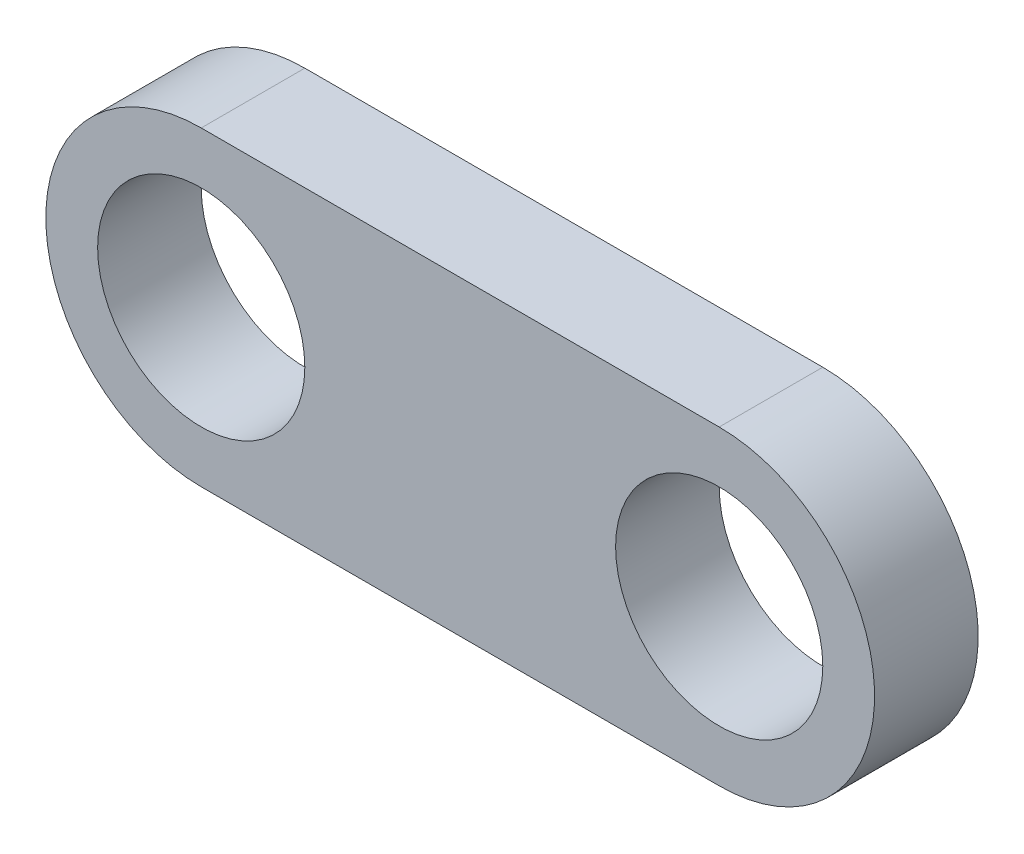
SolidWorks part; units mm, degrees
ref_plane "Front Plane" through (0, 0, 0) normal (0, 0, 1) x (1, 0, 0)
ref_plane "Top Plane" through (0, 0, 0) normal (0, 1, 0) x (1, 0, 0)
ref_plane "Right Plane" through (0, 0, 0) normal (1, 0, 0) x (0, 0, -1)
sketch "Sketch1" plane through (0, 0, 0) normal (0, 0, 1) x (1, 0, 0)
  line L0 (0, 0) -> (-50, 0) construction
  line L1 (0, -15) -> (-50, -15)
  line L2 (0, 15) -> (-50, 15)
  arc A0 (0, -15) -> (0, 15) centre (0, 0) ccw
  arc A1 (-50, 15) -> (-50, -15) centre (-50, 0) ccw
  circle A2 centre (-50, 0) radius 10
  circle A3 centre (0, 0) radius 10
  point P3 (-25, 0)
  dimension "D2" = 20
  dimension "D1" = 50
  dimension "D3" = 30
extrude "Boss-Extrude1" add sketch "Sketch1" along normal mid plane 10
